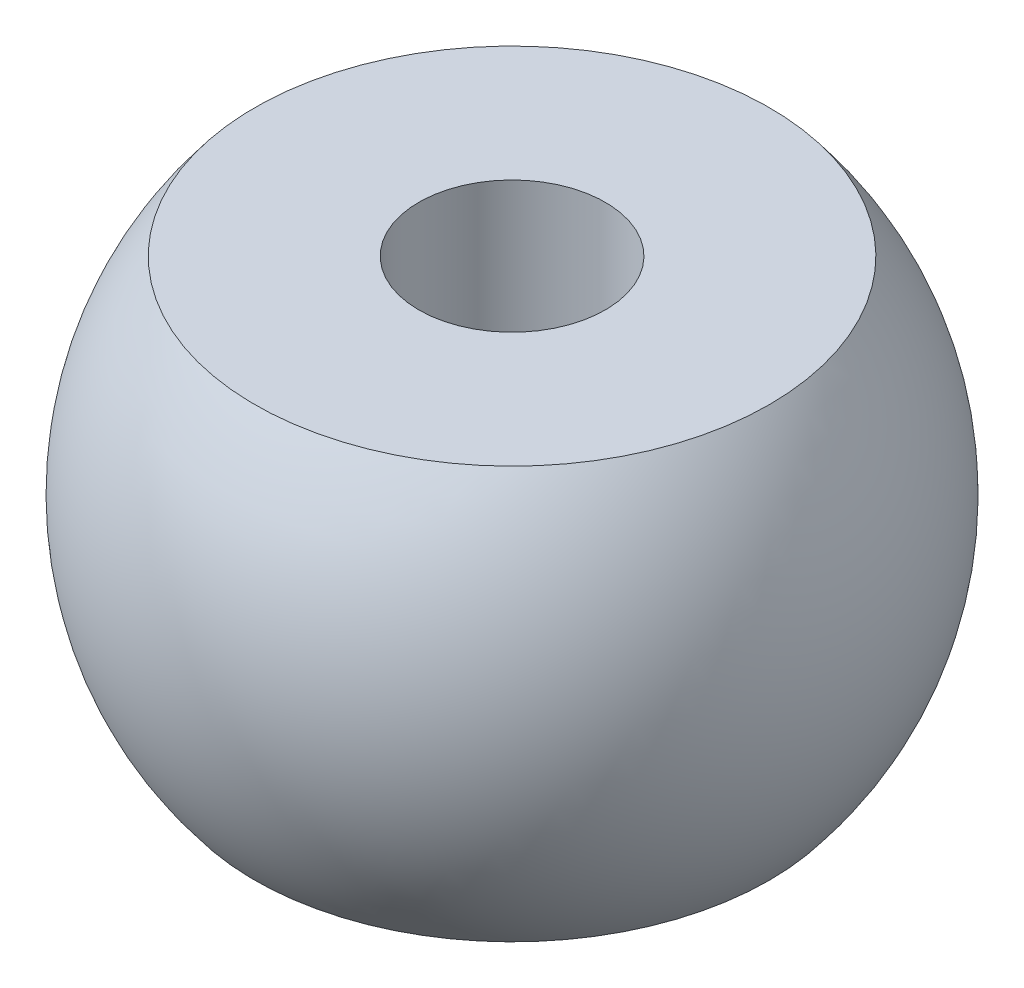
SolidWorks part; units mm, degrees
ref_plane "Front Plane" through (0, 0, 0) normal (0, 0, 1) x (1, 0, 0)
ref_plane "Top Plane" through (0, 0, 0) normal (0, 1, 0) x (1, 0, 0)
ref_plane "Right Plane" through (0, 0, 0) normal (1, 0, 0) x (0, 0, -1)
sketch "Sketch1" plane through (0, 0, 0) normal (0, 0, 1) x (1, 0, 0)
  line L0 (3, 6.625) -> (8.2746, 6.625)
  line L4 (3, 6.625) -> (3, -6.625)
  line L5 (0, 0) -> (3, -6.625) construction
  line L6 (0, 0) -> (3, 6.625) construction
  line L9 (3, -6.625) -> (8.2746, -6.625)
  line L10 (0, 6.625) -> (0, -6.625) construction
  arc A1 (8.2746, -6.625) -> (8.2746, 6.625) centre (0, 0) ccw
  point P0 (0, 0)
  dimension "D3" = 10.6
  dimension "D1" = 3
  dimension "D2" = 13.25
revolve "Revolve2" add sketch "Sketch1" angle 360 about L10
equation "\"shaft inner diameter\"= 15mm "
equation "\"shaft outer diameter\"= 20mm "
equation "\"column angle\" = 45deg "
equation "\"keyway_height\" = 1.39mm "
equation "\"keyway_width\" = 2.78mm "
equation "\"keyway_length\" = 30mm "
equation "\"steering column length\" = 555mm "
equation "\"steering wheel bolt width\" = 6mm "
equation "\"steering wheel bolt length\" = 40mm "
equation "\"bushing length\" = 40mm "
equation "\"bushing thickness\" = 3mm "
equation "\"u_joint clearance\" = 30mm "
equation "\"u_joint thickness\" = 7.5mm "
equation "\"horizontal shaft length\" = 90mm "
equation "\"short_bearing_outer_width\" = 10mm "
equation "\"column bushing diameter\" = \"primary shaft small diameter\" + 4 "
equation "\"column bushing distance\" = \"steering column length\"/4 "
equation "\"pinion width\" = 26.5mm "
equation "\"pin hole diameter\" = 10mm "
equation "\"rack hole to hole\" = 500mm "
equation "\"rack length\" = \"rack hole to hole\" + \"pin hole diameter\"*2 "
equation "\"pitch diameter\" = \"max travel\"/(pi * \"turn to lock\") "
equation "\"number of teeth\" = 18mm "
equation "\"module\" = \"pitch diameter\" / \"number of teeth\" "
equation "\"pressure angle\" = 20deg "
equation "\"D1@Sketch1\"=\"steering wheel bolt width\"/2"
equation "\"D2@Sketch1\"=\"pinion width\"/2"
equation "\"wheel base\" = 1561mm "
equation "\"track\" = 1354mm "
equation "\"turning radius\" = 2000mm "
equation "\"steering arm length\" = 100mm "
equation "\"turn to lock\" = 0.75mm "
equation "\"D3@Sketch1\"=\"pinion width\"/2.5"
equation "\"max turning angle\" = atn(\"wheel base\" / (\"turning radius\" - 0.5 * \"track\")) "
equation "\"max travel\" = 2 * \"steering arm length\" * sin(0.5 * \"max turning angle\") "
equation "\"primary shaft small diameter\" = 16mm "
equation "\"primary shaft large diameter\" = 24mm "
equation "\"secondary shaft small diameter\" = 16mm "
equation "\"secondary shaft large diameter\" = 25mm "
equation "\"tie rod length\" = 305mm "
equation "\"tie rod inner diameter\" = 6.6mm "
equation "\"tie rod outer diameter\" = 8.1mm "
equation "\"rack height\" = \"pin hole diameter\" * 2mm"
